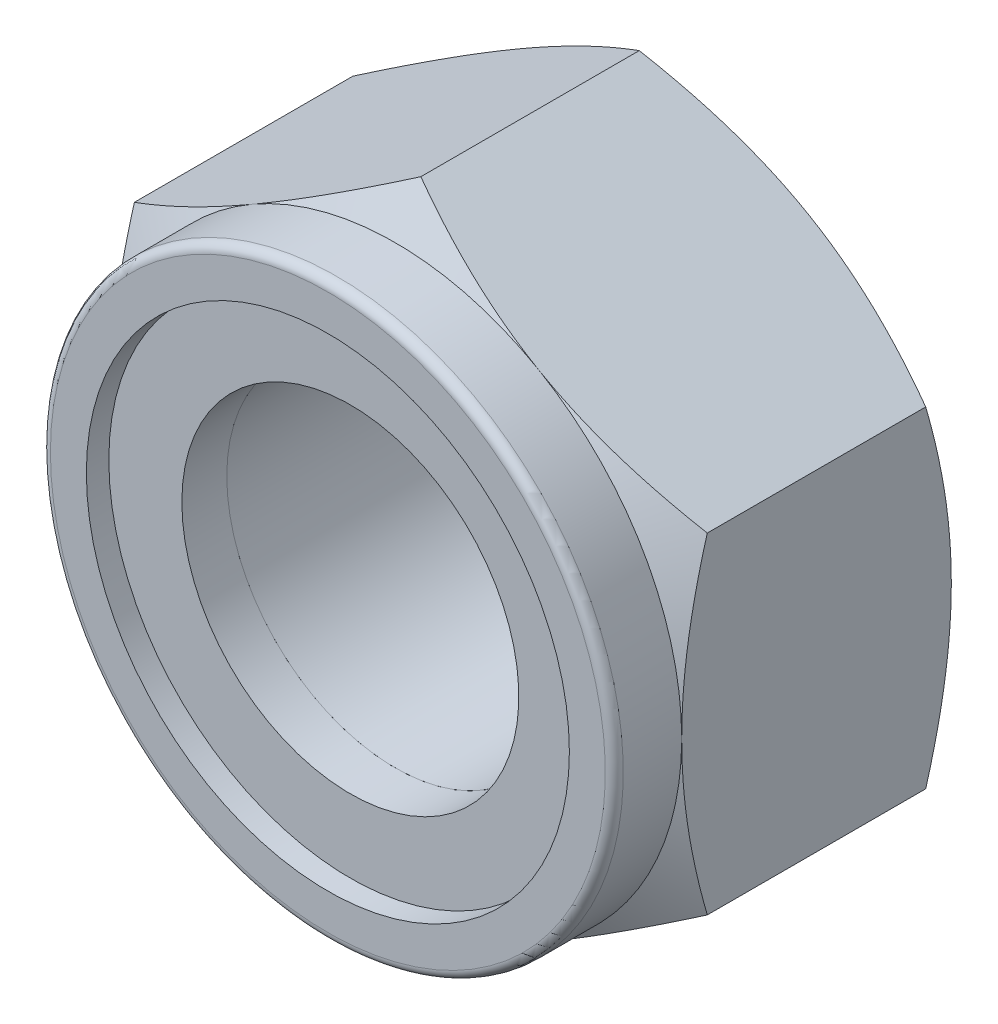
SolidWorks part; units mm, degrees
material "Stainless Steel (ferritic)"
ref_plane "Front" through (0, 0, 0) normal (0, 0, 1) x (1, 0, 0)
ref_plane "Top" through (0, 0, 0) normal (0, 1, 0) x (1, 0, 0)
ref_plane "Right" through (0, 0, 0) normal (1, 0, 0) x (0, 0, -1)
sketch "Sketch1" plane through (0, 0, 0) normal (0, 0, 1) x (1, 0, 0)
  line L1 (0, 9.815) -> (-8.5, 4.9075)
  line L2 (-8.5, 4.9075) -> (-8.5, -4.9075)
  line L3 (-8.5, -4.9075) -> (0, -9.815)
  line L4 (0, -9.815) -> (8.5, -4.9075)
  line L5 (8.5, -4.9075) -> (8.5, 4.9075)
  line L6 (8.5, 4.9075) -> (0, 9.815)
  circle A0 centre (0, 0) radius 8.5 construction
  dimension "S" = 17
extrude "Extrude1" add sketch "Sketch1" along normal blind 8
sketch "Sketch2" plane through (0, 0, 0) normal (0, 1, 0) x (1, 0, 0)
  line L0 (8.5, -8) -> (11.9, -8)
  line L1 (11.9, -8) -> (11.9, -6.037)
  line L2 (11.9, -6.037) -> (8.5, -8)
  line L3 (0, 0) -> (0, -8) construction
  dimension "D1" = 30
  dimension "D2" = 3.4
revolve "Cut-Revolve1" cut sketch "Sketch2" angle 360 about L3
ref_plane "Plane1" through (0, 0, 4) normal (0, 0, -1) x (-1, 0, 0)
mirror "Mirror1" about plane through (0, 0, 4) normal (0, 0, -1) of "Cut-Revolve1"
sketch "Sketch3" plane through (0, 0, 0) normal (0, 1, 0) x (1, 0, 0)
  line L0 (8.5, -8) -> (8.5, -10)
  line L1 (8.5, -10) -> (7.1667, -10)
  line L2 (7.1667, -10) -> (7.1667, -9.3333)
  line L3 (7.1667, -9.3333) -> (7.8333, -9.3333)
  line L4 (7.8333, -8) -> (7.8333, -9.3333)
  line L5 (4.25, -8) -> (8.5, -8) construction
  line L6 (8.5, 0) -> (0, 0) construction
  line L7 (8.5, -8) -> (7.8333, -8)
  line L8 (0, 0) -> (0, -8) construction
  line L9 (-4.25, -8) -> (4.25, -8) construction
  line L10 (4.25, 0) -> (-4.25, 0) construction
  dimension "m" = 10
  dimension "D1" = 0.6667
  dimension "D2" = 1.3333
revolve "Revolve1" add sketch "Sketch3" angle 360 about L8
sketch "Sketch4" plane through (0, 0, 0) normal (0, 0, -1) x (-1, 0, 0)
  circle A0 centre (0, 0) radius 5
  dimension "d" = 10
sketch "Sketch5" plane through (0, 0, 8) normal (0, 0, 1) x (1, 0, 0)
  circle A0 centre (0, 0) radius 7.8333
  circle A1 centre (0, 0) radius 5
  circle A2 centre (0, 0) radius 7.8333 construction
  dimension "D1" = 10
extrude "Extrude2" add sketch "Sketch5" along normal up to surface (1.3333 mm away) separate body up to face at (-7.1667, 0, 9.3333)
extrude "Cut-Extrude1" cut sketch "Sketch4" against normal through all
fillet "Fillet2" radius 0.2667 1 edges at (-8.5, 0, 10)
equation "\"D2@Sketch2\" = \"S@Sketch1\" / 5"
equation "\"D1@Sketch3\" = \"m@Sketch3\" / 15"
equation "\"D2@Sketch3\" = \"D1@Sketch3\" * 2"
equation "\"D1@Sketch5\" = \"d@Sketch4\""
equation "\"D1@Fillet2\" = \"D2@Sketch3\" / 5"
equation "\"D1@Plane1\" = \"m2@Extrude1\" / 2"
